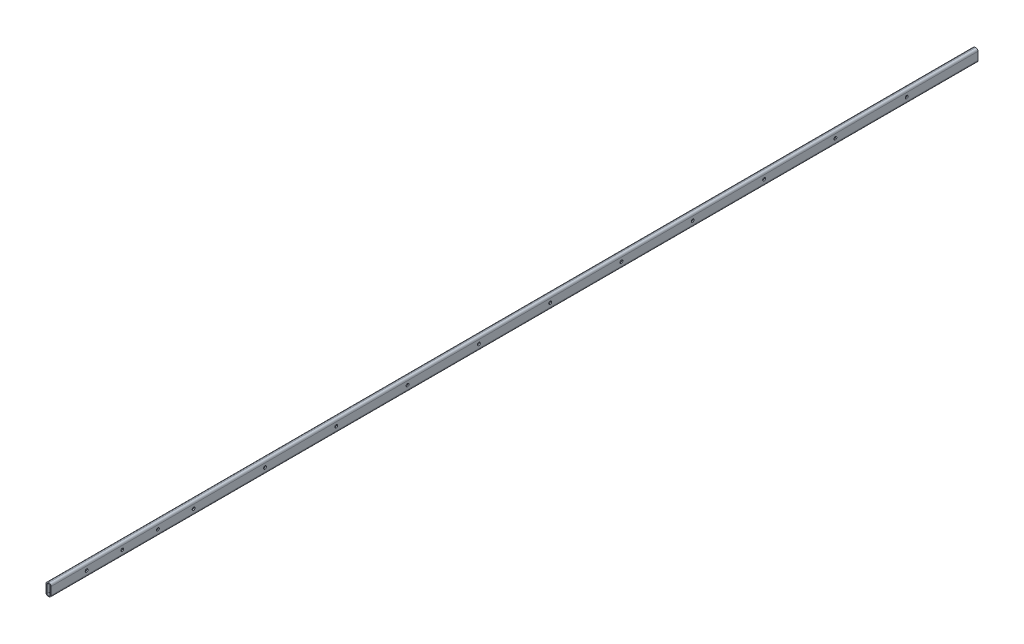
SolidWorks part; units mm, degrees
ref_plane "前视基准面" through (0, 0, 0) normal (0, 0, 1) x (1, 0, 0)
ref_plane "上视基准面" through (0, 0, 0) normal (0, 1, 0) x (1, 0, 0)
ref_plane "右视基准面" through (0, 0, 0) normal (1, 0, 0) x (0, 0, -1)
sketch "草图2" plane through (0, 0, 0) normal (0, 0, 1) x (1, 0, 0)
  line L1 (-0.5, 8.5) -> (0.5, 8.5)
  line L2 (-3.5, 5.5) -> (-3.5, -5.5)
  line L3 (-0.5, -8.5) -> (0.5, -8.5)
  line L4 (3.5, 5.5) -> (3.5, -5.5)
  line L5 (-3.5, 8.5) -> (3.5, -8.5) construction
  line L6 (-3.5, -8.5) -> (3.5, 8.5) construction
  arc A0 (0.5, 8.5) -> (3.5, 5.5) centre (0.5, 5.5) cw
  arc A1 (-0.5, 8.5) -> (-3.5, 5.5) centre (-0.5, 5.5) ccw
  arc A2 (-3.5, -5.5) -> (-0.5, -8.5) centre (-0.5, -5.5) ccw
  arc A3 (0.5, -8.5) -> (3.5, -5.5) centre (0.5, -5.5) ccw
  point P0 (0, 0)
  point P17 (3.5, 0)
  dimension "D1" = 3
  dimension "D2" = 3
  dimension "D3" = 3
  dimension "D4" = 3
  dimension "D5" = 1
  dimension "D6" = 5.5
extrude "凸台-拉伸1" add sketch "草图2" along normal blind 1300
sketch "草图3" plane through (-3.5, 0, 0) normal (-1, 0, 0) x (0, 0, 1)
  circle A0 centre (100, 0) radius 2
  circle A1 centre (200, 0) radius 2
  circle A2 centre (300, 0) radius 2
  circle A3 centre (400, 0) radius 2
  circle A4 centre (500, 0) radius 2
  circle A5 centre (600, 0) radius 2
  circle A6 centre (700, 0) radius 2
  circle A7 centre (800, 0) radius 2
  circle A8 centre (900, 0) radius 2
  circle A9 centre (1000, 0) radius 2
extrude "切除-拉伸1" cut sketch "草图3" against normal through all
sketch "草图4" plane through (0, 0, 0) normal (0, 0, -1) x (-1, 0, 0)
  line L0 (-0.5, 8.5) -> (0.5, 8.5) construction
  line L1 (-0.5, 7) -> (0.5, 7)
  line L2 (-2, 5.5) -> (-2, -5.9028)
  line L3 (-0.9028, -7) -> (0.9028, -7)
  line L4 (2, 5.5) -> (2, -5.9028)
  line L5 (0.5, -8.5) -> (-0.5, -8.5) construction
  line L6 (-3.5, -5.5) -> (-3.5, 5.5) construction
  line L7 (3.5, 5.5) -> (3.5, -5.5) construction
  arc A0 (-2, 5.5) -> (-0.5, 7) centre (-0.5, 5.5) cw
  arc A1 (2, 5.5) -> (0.5, 7) centre (0.5, 5.5) ccw
  arc A2 (2, -5.9028) -> (0.9028, -7) centre (0.9028, -5.9028) cw
  arc A3 (-0.9028, -7) -> (-2, -5.9028) centre (-0.9028, -5.9028) cw
  dimension "D5" = 1.5
  dimension "D6" = 1.5
  dimension "D7" = 1.0972
  dimension "D1" = 1.5
  dimension "D2" = 1.5
  dimension "D3" = 1.5
  dimension "D4" = 1.5
extrude "切除-拉伸2" cut sketch "草图4" against normal blind 1500
sketch "草图5" plane through (-3.5, 0, 0) normal (-1, 0, 0) x (0, 0, 1)
  circle A1 centre (1100, 0) radius 2
  circle A2 centre (1200, 0) radius 2
  circle A3 centre (1250, 0) radius 2
  circle A4 centre (1150, 0) radius 2
extrude "切除-拉伸3" cut sketch "草图5" against normal through all
